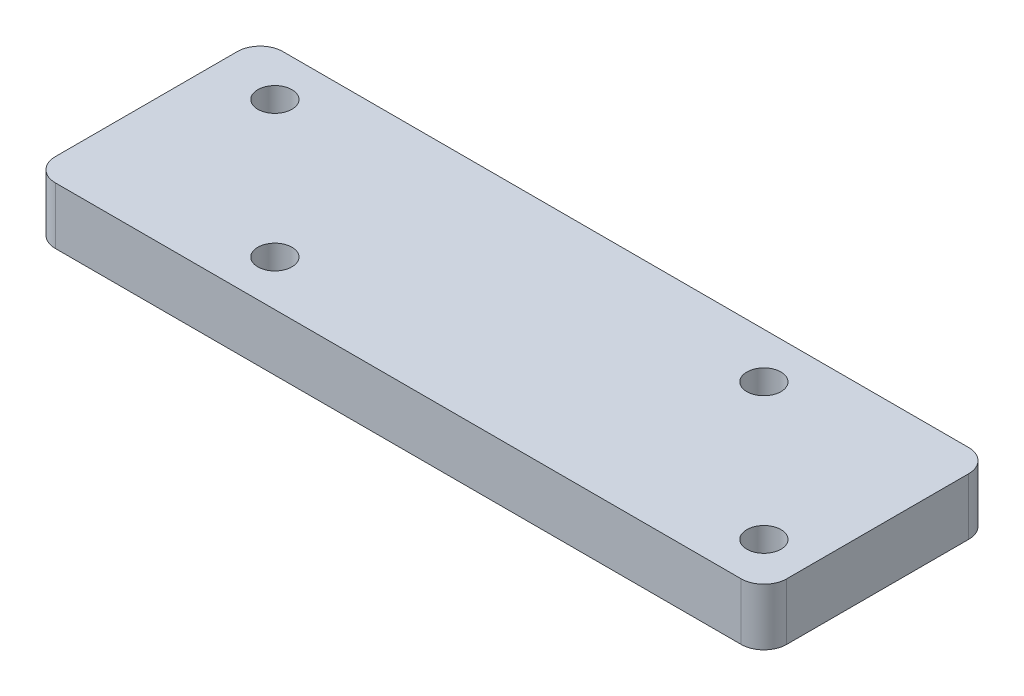
SolidWorks part; units mm, degrees
ref_plane "前视基准面" through (0, 0, 0) normal (0, 0, 1) x (1, 0, 0)
ref_plane "上视基准面" through (0, 0, 0) normal (0, 1, 0) x (1, 0, 0)
ref_plane "右视基准面" through (0, 0, 0) normal (1, 0, 0) x (0, 0, -1)
sketch "草图1" plane through (0, 0, 0) normal (0, 1, 0) x (1, 0, 0)
  line L0 (5.3, 16) -> (48.3, 16) construction
  line L1 (0, 0) -> (64.3, 0)
  line L2 (0, 0) -> (0, 20)
  line L3 (0, 20) -> (64.3, 20)
  line L4 (64.3, 0) -> (64.3, 20)
  circle A0 centre (5.3, 16) radius 1.5
  circle A1 centre (17.3, 4) radius 1.5
  circle A2 centre (48.3, 16) radius 1.5
  circle A3 centre (60.3, 4) radius 1.5
  dimension "D1" = 3
  dimension "D2" = 5.3
  dimension "D4" = 12
  dimension "D5" = 4
  dimension "D6" = 12
  dimension "D3" = 20
  dimension "D7" = 64.3
  dimension "D9" = 43
  dimension "D8" = 2
extrude "凸台-拉伸1" add sketch "草图1" along normal blind 5
fillet "圆角1" radius 2 4 edges at (0, 2.5, 0) (0, 2.5, -20) (64.3, 2.5, -20) (64.3, 2.5, 0)
